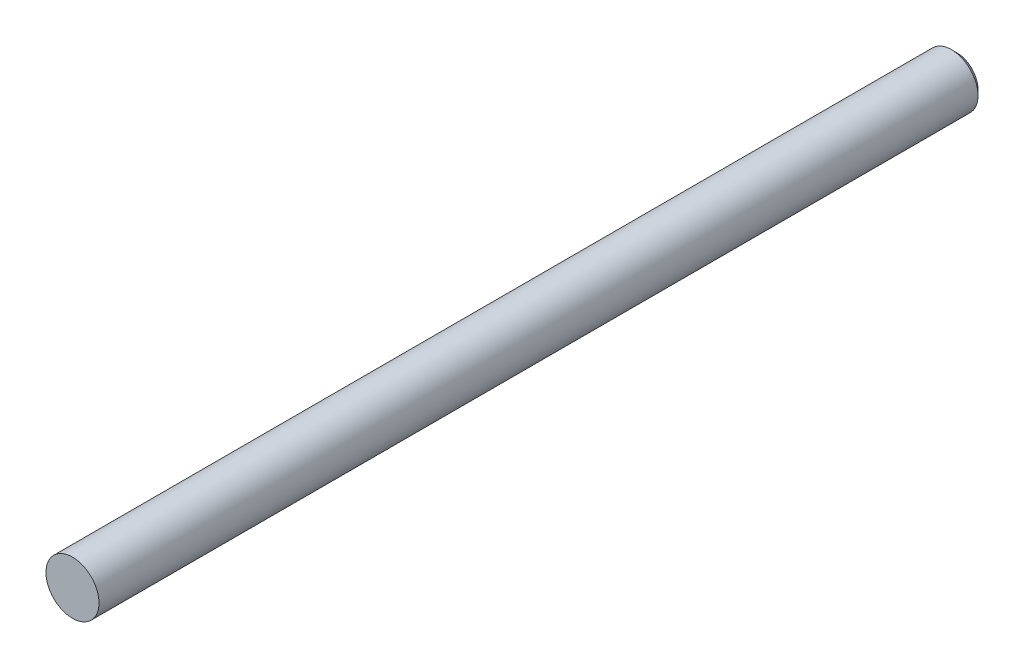
SolidWorks part; units mm, degrees
ref_plane "Front" through (0, 0, 0) normal (0, 0, 1) x (1, 0, 0)
ref_plane "Top" through (0, 0, 0) normal (0, 1, 0) x (1, 0, 0)
ref_plane "Right" through (0, 0, 0) normal (1, 0, 0) x (0, 0, -1)
sketch "Sketch1" plane through (0, 0, 0) normal (0, 0, 1) x (1, 0, 0)
  circle A0 centre (0, 0) radius 3
  dimension "dia" = 6
extrude "Extrude1" add sketch "Sketch1" along normal mid plane 200
sketch "Sketch2" plane through (0, 0, 0) normal (1, 0, 0) x (0, 0, -1)
  point P0 (-100, 3)
  point P1 (100, 3)
chamfer "Chamfer1" distance 0.6 angle 45 2 edges at (3, 0, -100) (3, 0, 100)
ref_plane "Plane1" through (0, 0, 100) normal (0, 0, 1) x (1, 0, 0)
sketch "Sketch3" plane through (0, 0, 100) normal (0, 0, 1) x (1, 0, 0)
  circle A0 centre (0, 0) radius 10.4354
extrude "Cut-Extrude1" cut sketch "Sketch3" against normal blind 100
equation "\"D1@Chamfer1\" = \"dia@Sketch1\" * .1"
